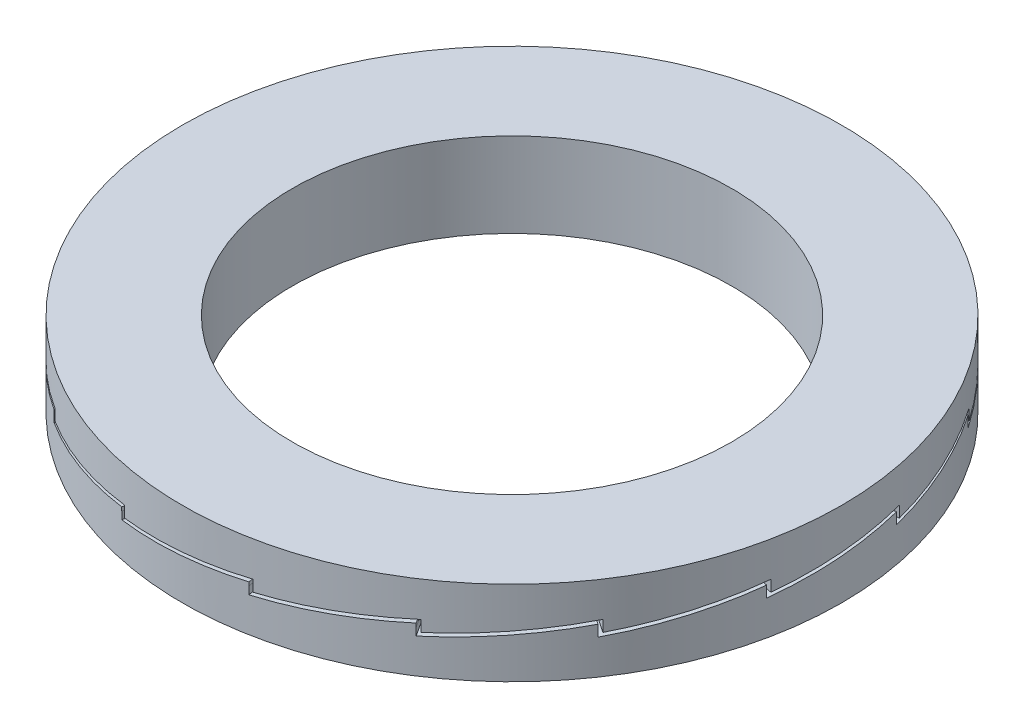
SolidWorks part; units mm, degrees
material "PW100:Mi:0:30:Re:13:"
ref_plane "Front" through (0, 0, 0) normal (0, 0, 1) x (1, 0, 0)
ref_plane "Top" through (0, 0, 0) normal (0, 1, 0) x (1, 0, 0)
ref_plane "Right" through (0, 0, 0) normal (1, 0, 0) x (0, 0, -1)
sketch "Support-Top-Body" plane through (0, 0, 0) normal (0, 1, 0) x (1, 0, 0)
  line L0 (0, 0) -> (6.5, 0) construction
  line L1 (6.5, 0) -> (9.75, 0) construction
  circle A0 centre (0, 0) radius 9.75
  circle A1 centre (0, 0) radius 6.5
  dimension "Diam-Inner" = 13
  dimension "Diam-Outer" = 19.5
sketch "Support-Front-Body" plane through (0, 0, 0) normal (0, 0, 1) x (1, 0, 0)
  line L0 (6.5, 1.15) -> (6.6, 1.25)
  line L1 (6.5, 1.25) -> (9.75, 1.25)
  line L2 (6.5, 1.25) -> (6.5, -1.25)
  line L3 (6.5, -1.25) -> (9.75, -1.25)
  line L4 (9.75, 1.25) -> (9.75, -1.25)
  line L5 (0, -1.25) -> (0, 1.25) construction
  line L6 (6.5, 1.25) -> (0, 1.25) construction
  line L7 (6.5, -1.25) -> (0, -1.25) construction
  line L8 (6.5, -1.15) -> (6.6, -1.25)
  line L9 (9.75, 0) -> (0, 0) construction
  dimension "Thickness" = 2.5
  dimension "Angel-Cut" = 45
  dimension "Dist-Cut" = 0.1
sketch "Sketch3" plane through (0, 0, 0) normal (0, 0, 1) x (1, 0, 0)
  line L0 (0, -1.25) -> (0, 1.25) construction
  line L1 (0, -1.25) -> (0, 1.25) construction
  line L4 (9.75, 1.25) -> (6.5, 1.25)
  line L5 (9.75, -1.25) -> (9.75, 1.25)
  line L6 (6.5, -1.25) -> (9.75, -1.25)
  line L7 (6.5, 1.25) -> (6.5, -1.25)
  line L8 (9.75, 1.25) -> (6.5, 1.25)
  line L9 (9.75, -1.25) -> (9.75, 1.25)
  line L10 (6.5, -1.25) -> (9.75, -1.25)
  line L11 (6.5, 1.25) -> (6.5, -1.25)
  dimension "D1" = 0
revolve "Base-Revolve" add sketch "Sketch3" angle 360 about L1
sketch "Support-Top-Cut" plane through (0, 0, 0) normal (0, 1, 0) x (1, 0, 0)
  line L0 (8.9656, 0) -> (9.75, 0)
  line L1 (8.9656, 0) -> (8.9656, 8.9656) construction
  line L3 (8.9656, 8.9656) -> (0, 8.9656) construction
  line L5 (8.9656, 8.9656) -> (9.75, 0) construction
  line L6 (0, 0) -> (0, 8.9656) construction
  line L7 (0, 0) -> (8.9656, 0) construction
  line L8 (0, 0) -> (8.7933, 1.7491) construction
  line L9 (0, 0) -> (8.7933, -1.7491) construction
  line L10 (8.7933, 1.7491) -> (9.75, 1.9394)
  line L11 (8.7933, -1.7491) -> (9.75, -1.9394)
  line L12 (8.9656, -1.7834) -> (8.9656, 1.7834) construction
  line L13 (9.75, -1.9394) -> (9.75, 1.9394) construction
  circle A0 centre (0, 0) radius 8.9656 construction
  dimension "Angle-Cut-Length" = 5
ref_plane "Plane-Cut-Start" through (8.9656, 0, 0) normal (1, 0, 0) x (0, 0, -1)
ref_plane "Plane-Cut-End" through (9.75, 0, 0) normal (1, 0, 0) x (0, 0, -1)
sketch "Support-Plane-Cut-Start" plane through (8.9656, 0, 0) normal (1, 0, 0) x (0, 0, -1)
  line L0 (-1.8815, 0) -> (-1.7834, 0)
  line L1 (-1.7834, 0) -> (-1.7834, -0.1068)
  line L2 (-1.7834, -0.1068) -> (1.7834, 0.2053)
  line L3 (1.7834, 0.2053) -> (1.7834, 0)
  line L4 (1.7834, 0) -> (1.6852, 0)
  line L5 (1.6852, 0) -> (1.6852, 0.0982)
  line L6 (1.6852, 0.0982) -> (-1.8815, -0.2139)
  line L7 (-1.8815, -0.2139) -> (-1.8815, 0)
  line L8 (6.5, 0) -> (-6.5, 0) construction
  line L13 (1.6852, 0.0982) -> (1.6766, 0.196) construction
  line L14 (0, -0.0493) -> (0, 0.0493) construction
  dimension "Angle-Cut" = 5
sketch "Sketch12" plane through (8.9656, 0, 0) normal (1, 0, 0) x (0, 0, -1)
  line L8 (-1.8815, -0.2139) -> (1.6852, 0.0982)
  line L9 (1.6852, 0.0982) -> (1.6852, 0)
  line L10 (1.6852, 0) -> (1.7834, 0)
  line L11 (1.7834, 0) -> (1.7834, 0.2053)
  line L12 (1.7834, 0.2053) -> (-1.7834, -0.1068)
  line L13 (-1.7834, -0.1068) -> (-1.7834, 0)
  line L14 (-1.7834, 0) -> (-1.8815, 0)
  line L15 (-1.8815, 0) -> (-1.8815, -0.2139)
  line L16 (-1.8815, -0.2139) -> (1.6852, 0.0982)
  line L17 (1.6852, 0.0982) -> (1.6852, 0)
  line L18 (1.6852, 0) -> (1.7834, 0)
  line L19 (1.7834, 0) -> (1.7834, 0.2053)
  line L20 (1.7834, 0.2053) -> (-1.7834, -0.1068)
  line L21 (-1.7834, -0.1068) -> (-1.7834, 0)
  line L22 (-1.7834, 0) -> (-1.8815, 0)
  line L23 (-1.8815, 0) -> (-1.8815, -0.2139)
  dimension "D1" = 0
sketch "Sketch15" plane through (9.75, 0, 0) normal (1, 0, 0) x (0, 0, -1)
  line L0 (-2.0501, 0) -> (-1.9394, 0)
  line L1 (-1.9394, 0) -> (-1.9394, -0.1204)
  line L2 (-1.9394, -0.1204) -> (1.9394, 0.2189)
  line L3 (1.9394, 0.2189) -> (1.9394, 0)
  line L4 (1.9394, 0) -> (1.8287, 0)
  line L5 (1.8287, 0) -> (1.8287, 0.1107)
  line L6 (1.8287, 0.1107) -> (-2.0501, -0.2286)
  line L7 (-2.0501, -0.2286) -> (-2.0501, 0)
  line L8 (-1.9394, 0) -> (1.9394, 0) construction
  line L9 (-1.8815, -0.2139) -> (1.6852, 0.0982) construction
  line L10 (8.9656, 0) -> (-8.9656, 0) construction
  line L11 (1.7834, 0.2053) -> (-1.7834, -0.1068) construction
loft "Cut-Profile" cut profiles "Sketch12", "Sketch15"
pattern_circular "Pattern-Cut-Profile" count 16 every 22.5 about axis through (0, -1.25, 0) along (0, 1, 0) of "Cut-Profile"
sketch "Sketch17" plane through (0, 0, 0) normal (0, 0, 1) x (1, 0, 0)
  line L0 (6.5, 1.25) -> (6.5, -1.25) construction
  line L1 (6.5, 1.25) -> (9.75, 1.25) construction
  line L2 (6.5, 1.15) -> (6.6, 1.25) construction
  line L4 (6.5, 1.25) -> (6.6, 1.25)
  line L5 (6.5, 1.15) -> (6.6, 1.25)
  line L6 (0, 0) -> (0, 1.25) construction
  line L7 (0, -1.25) -> (0, 1.25) construction
  line L8 (6.5, -1.15) -> (6.6, -1.25) construction
  line L9 (6.5, -1.25) -> (9.75, -1.25) construction
  line L10 (6.5, -1.15) -> (6.6, -1.25)
  line L11 (6.5, -1.25) -> (6.6, -1.25)
  line L12 (6.5, 1.25) -> (6.5, 1.15)
  line L13 (6.5, -1.15) -> (6.5, -1.25)
revolve "Cosmetic-Cut" [suppressed] cut sketch "Sketch17" angle 360 about L6
equation "\"Num-Cut-Profile@Pattern-Cut-Profile\" =360 / \"Angle-Cut-Width@Pattern-Cut-Profile\""
